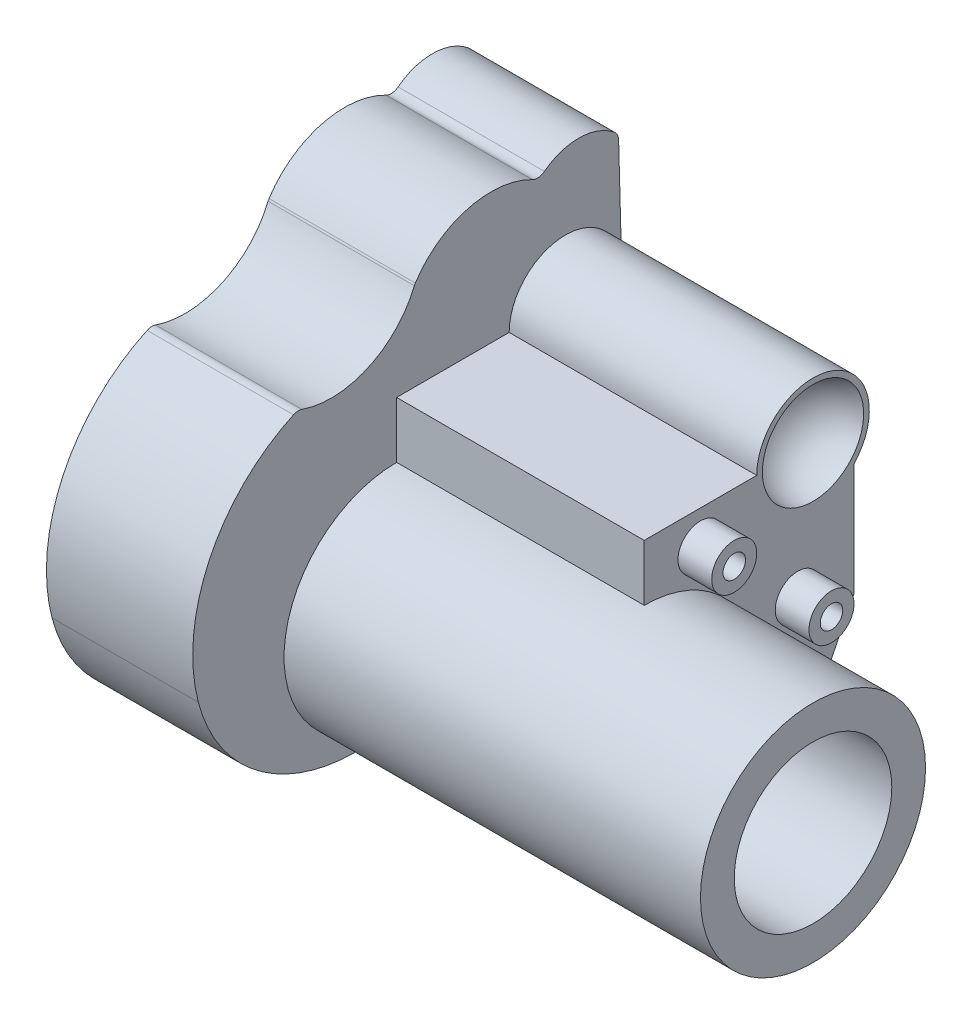
SolidWorks part; units mm, degrees
ref_plane "Front Plane" through (0, 0, 0) normal (0, 0, 1) x (1, 0, 0)
ref_plane "Top Plane" through (0, 0, 0) normal (0, 1, 0) x (1, 0, 0)
ref_plane "Right Plane" through (0, 0, 0) normal (1, 0, 0) x (0, 0, -1)
sketch "Sketch1" plane through (0, 0, 0) normal (1, 0, 0) x (0, 0, -1)
  circle A0 centre (0, 0) radius 10
  dimension "D1" = 20
extrude "Boss-Extrude1" add sketch "Sketch1" against normal blind 50
ref_plane "Plane1" through (-50, 0, 0) normal (1, 0, 0) x (0, 0, -1)
sketch "Sketch3" plane through (-50, 0, 0) normal (1, 0, 0) x (0, 0, -1)
  line L0 (0, 10) -> (0, 15)
  line L1 (0, 15) -> (10, 15)
  line L2 (18.6427, 11.575) -> (18.6427, 1.575)
  line L3 (18.6427, 1.575) -> (18.6427, -2.425) construction
  line L4 (18.6427, -2.425) -> (16.6427, -2.425) construction
  line L5 (16.6427, -2.425) -> (16.6427, -9.9978)
  line L6 (0, -10) -> (10, -10)
  line L7 (18.6427, 1.575) -> (16.6427, -2.425)
  line L8 (0, 10) -> (0, -10)
  circle A0 centre (0, 0) radius 10 construction
  arc A1 (10, 15) -> (18.6427, 11.575) centre (15, 15) cw
  arc A2 (10, -10) -> (16.6427, -9.9978) centre (13.32, -6) ccw
  point P6 (15, 15)
  point P17 (13.32, -6)
  dimension "D3" = 5
  dimension "D8" = 4
  dimension "D10" = 7.5727
  dimension "D1" = 5
  dimension "D2" = 10
  dimension "D4" = 3.6427
  dimension "D5" = 10
  dimension "D6" = 4
  dimension "D7" = 2
  dimension "D9" = 10
  dimension "D11" = 3.32
extrude "Boss-Extrude3" add sketch "Sketch3" along normal blind 35 contours L1 A1 L2 L7 L5 A2 L6 L8 L0
sketch "Sketch6" plane through (-15, 0, 0) normal (1, 0, 0) x (0, 0, -1)
  line L0 (13.3218, -1.4483) -> (13.3218, -10.9483) construction
  line L1 (13.3218, -1.4483) -> (13.3218, -10.9483)
  arc A0 (10, -10) -> (16.6427, -9.9978) centre (13.32, -6) ccw construction
  arc A1 (13.3218, -10.9483) -> (13.3218, -1.4483) centre (13.3218, -6.1983) ccw
  point P0 (13.3218, -6.1983)
  point P1 (13.3218, -6.1983)
  point P2 (10, -10)
  point P7 (13.3218, -11.1983)
  dimension "D2" = 9.5
  dimension "D1" = 5
revolve "Cut-Revolve1" cut sketch "Sketch6" angle 360 about L0
sketch "Sketch7" plane through (-15, 0, 0) normal (1, 0, 0) x (0, 0, -1)
  line L0 (15, 15) -> (15, 20) construction
  line L1 (15, 10.5) -> (15, 19.5)
  line L2 (15, 19.5) -> (15, 10.5) construction
  arc A0 (18.6427, 11.575) -> (10, 15) centre (15, 15) ccw construction
  arc A1 (15, 10.5) -> (15, 19.5) centre (15, 15) ccw
  point P0 (15, 15)
  dimension "D2" = 9
  dimension "D1" = 5
revolve "Cut-Revolve2" cut sketch "Sketch7" angle 360 about L1
sketch "Sketch8" plane through (-15, 0, 0) normal (1, 0, 0) x (0, 0, -1)
  line L0 (18.6427, 11.575) -> (18.6427, 1.575) construction
  arc A0 (10, -10) -> (16.6427, -9.9978) centre (13.32, -6) ccw construction
  circle A1 centre (13.6427, 3.8017) radius 2
  circle A2 centre (13.6427, 3.8017) radius 1
  circle A3 centre (5, 12) radius 2
  circle A4 centre (5, 12) radius 1
  point P0 (13.6427, 3.8017)
  point P4 (13.3218, -11.1983)
  point P7 (18.6427, 6.575)
  point P11 (5, 12)
  dimension "D3" = 2
  dimension "D4" = 4
  dimension "D7" = 4
  dimension "D8" = 2
  dimension "D1" = 15
  dimension "D2" = 5
  dimension "D5" = 5
  dimension "D6" = 3
extrude "Boss-Extrude4" add sketch "Sketch8" along normal blind 3
sketch "Sketch10" plane through (-50, 0, 0) normal (-1, 0, 0) x (0, 0, 1)
  line L1 (-20, 15) -> (-19.7146, 25.4001)
  line L7 (0, 10) -> (0, 15)
  line L8 (0, 15) -> (-10, 15)
  line L9 (-18.6427, 11.575) -> (-18.6427, 1.575)
  line L10 (-18.6427, 1.575) -> (-16.6427, -2.425)
  line L11 (-16.6427, -2.425) -> (-16.6427, -9.9978)
  line L12 (-10, -10) -> (0, -10)
  line L13 (0, 10) -> (0, 15)
  line L14 (0, 15) -> (-10, 15)
  arc A0 (0, -10) -> (17.6188, 0.3451) centre (3.6369, 3.982) ccw
  arc A1 (17.6188, 0.3451) -> (8.7799, 18.4164) centre (2.6737, 4.2325) ccw
  arc A2 (8.7799, 18.4164) -> (-1.6118, 22.89) centre (5.8208, 25.849) cw
  arc A3 (-1.6118, 22.89) -> (-12.6435, 25.4001) centre (-8.3827, 18.6292) ccw
  arc A4 (-12.6435, 25.4001) -> (-19.7146, 25.4001) centre (-16.1791, 21.8645) ccw
  arc A6 (-10, 15) -> (-18.6427, 11.575) centre (-15, 15) ccw construction
  arc A10 (0, -10) -> (0, 10) centre (0, 0) ccw
  arc A11 (-10, 15) -> (-18.6427, 11.575) centre (-15, 15) ccw
  arc A12 (-16.6427, -9.9978) -> (-10, -10) centre (-13.32, -6) ccw
  arc A13 (0, -10) -> (0, 10) centre (0, 0) ccw
  arc A14 (-10, 15) -> (-20, 15) centre (-15, 15) ccw
  arc M2 (0, -10) -> (0, 10) centre (0, 0) ccw
  line M3 (0, 10) -> (0, 15)
  line M4 (0, 15) -> (-10, 15)
  arc M5 (-10, 15) -> (-18.6427, 11.575) centre (-15, 15) ccw
  dimension "D1" = 5
  dimension "D2" = 8
  dimension "D3" = 8
  dimension "D4" = 15.4424
  dimension "D5" = 14.4472
  dimension "D6" = 10.4001
  dimension "D7" = 10
  dimension "D8" = 6.8645
  dimension "D9" = 3.6292
  dimension "D10" = 10.7675
  dimension "D11" = 11.018
  dimension "D12" = 10.849
  dimension "D13" = 6.1791
  dimension "D14" = 1.6173
  dimension "D15" = 15.8208
  dimension "D16" = 0
extrude "Boss-Extrude6" add sketch "Sketch10" against normal blind 13 contours A3 A4 L1 A0 A1 A2 M5 M4 M3 M2
fillet "Fillet1" radius 1 3 edges at (-43.5, 18.4164, 8.7799) (-43.5, 22.89, -1.6118) (-43.5, 25.4001, -12.6435)
fillet "Fillet2" radius 1 1 edges at (-43.5, 25.4001, -19.7146)
sketch "Sketch11" plane through (0, 0.5597, -20.3963) normal (0, 0.0274, -0.9996) x (-1, 0, 0)
  line L0 (50, 14.72) -> (50, 24.4253) construction
  line L1 (50, 24.0727) -> (50, 15.0727) construction
  line L2 (50, 24.0727) -> (50, 15.0727)
  arc A0 (50, 24.0727) -> (50, 15.0727) centre (50, 19.5727) ccw
  dimension "D1" = 9
revolve "Cut-Revolve3" cut sketch "Sketch11" angle 360 about L1
sketch "Sketch2" plane through (0, 0, 0) normal (1, 0, 0) x (0, 0, -1)
  circle A0 centre (0, 0) radius 7
  circle A1 centre (0, 0) radius 10
  circle A2 centre (0, 0) radius 10 construction
  dimension "D1" = 0
  dimension "D2" = 3
extrude "Cut-Extrude2" cut sketch "Sketch2" against normal through all
